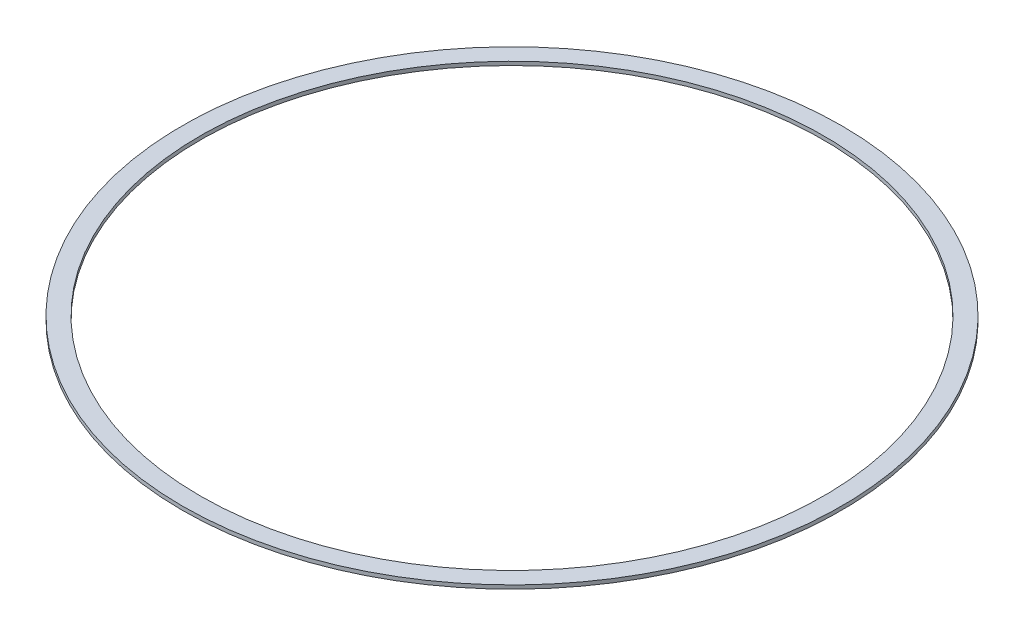
SolidWorks part; units mm, degrees
material "Duranickel(R) 301"
ref_plane "Front Plane" through (0, 0, 0) normal (0, 0, 1) x (1, 0, 0)
ref_plane "Top Plane" through (0, 0, 0) normal (0, 1, 0) x (1, 0, 0)
ref_plane "Right Plane" through (0, 0, 0) normal (1, 0, 0) x (0, 0, -1)
sketch "Sketch1" plane through (0, 0, 0) normal (0, 1, 0) x (1, 0, 0)
  circle A0 centre (0, 0) radius 212.8774
  circle A1 centre (0, 0) radius 224.9678
  dimension "D1" = 449.9356
  dimension "D2" = 425.7548
extrude "Boss-Extrude1" add sketch "Sketch1" along normal blind 2.54
ref_plane "Plane1" through (0, 1.27, 0) normal (0, 1, 0) x (1, 0, 0)
